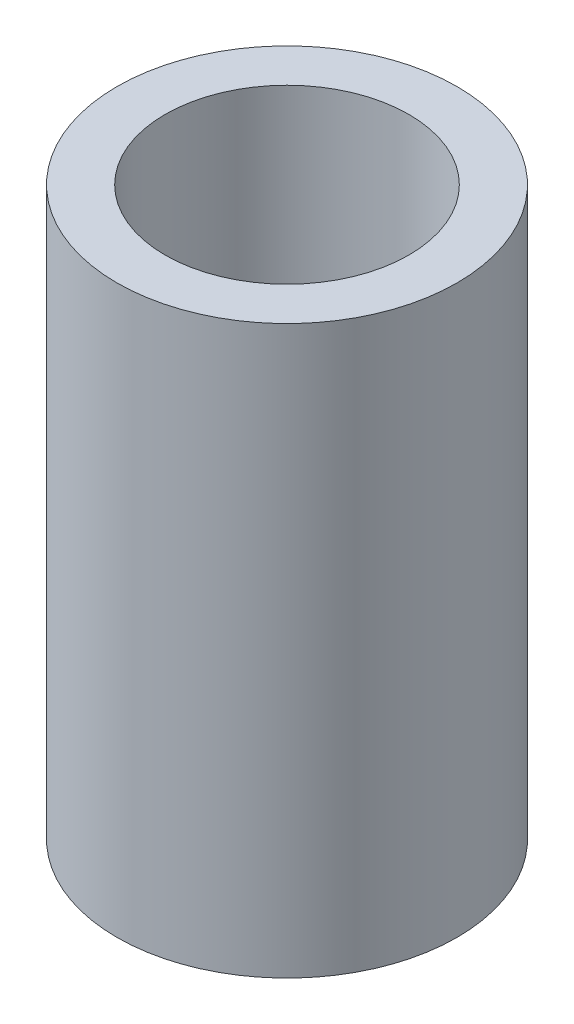
SolidWorks part; units mm, degrees
ref_plane "Alzado" through (0, 0, 0) normal (0, 0, 1) x (1, 0, 0)
ref_plane "Planta" through (0, 0, 0) normal (0, 1, 0) x (1, 0, 0)
ref_plane "Vista lateral" through (0, 0, 0) normal (1, 0, 0) x (0, 0, -1)
sketch "Croquis1" plane through (0, 0, 0) normal (0, 1, 0) x (1, 0, 0)
  circle A0 centre (0, 0) radius 6
  circle A1 centre (0, 0) radius 4.3
extrude "Saliente-Extruir1" add sketch "Croquis1" along normal blind 20
